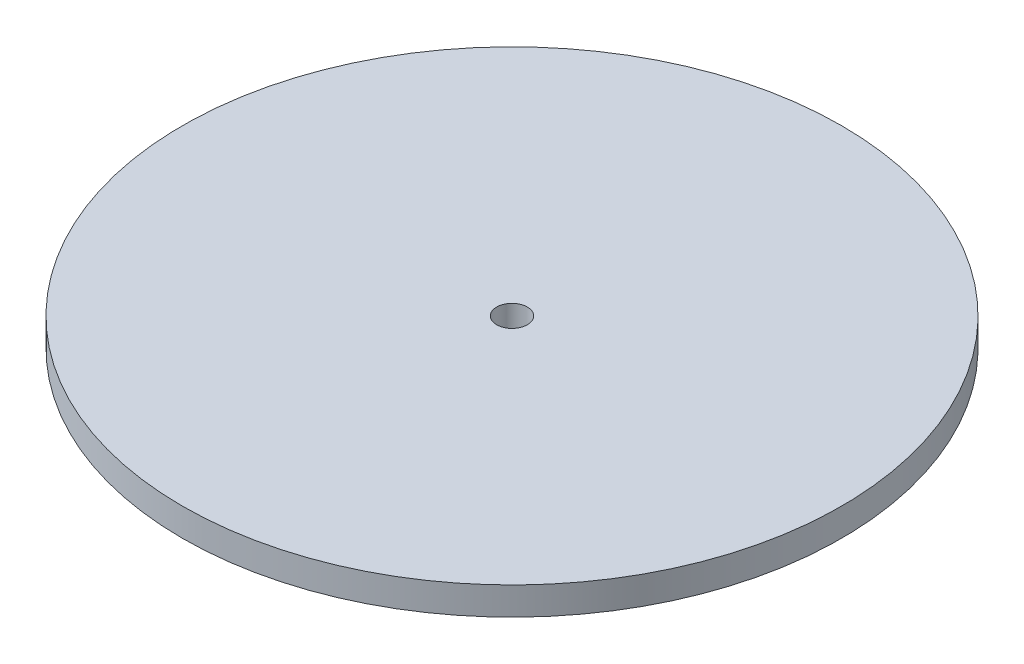
SolidWorks part; units mm, degrees
ref_plane "Plan de face" through (0, 0, 0) normal (0, 0, 1) x (1, 0, 0)
ref_plane "Plan de dessus" through (0, 0, 0) normal (0, 1, 0) x (1, 0, 0)
ref_plane "Plan de droite" through (0, 0, 0) normal (1, 0, 0) x (0, 0, -1)
sketch "Esquisse1" plane through (0, 0, 0) normal (0, 1, 0) x (1, 0, 0)
  circle A0 centre (0, 0) radius 75
extrude "Boss.-Extru.1" add sketch "Esquisse1" along normal blind 6.35
sketch "Esquisse2" plane through (0, 6.35, 0) normal (0, 1, 0) x (1, 0, 0)
  circle A0 centre (0, 0) radius 3.5
  dimension "D1" = 7
extrude "Enlèv. mat.-Extru.1" cut sketch "Esquisse2" against normal up to surface (6.35 mm away) up to face at (0, 0, 75)
